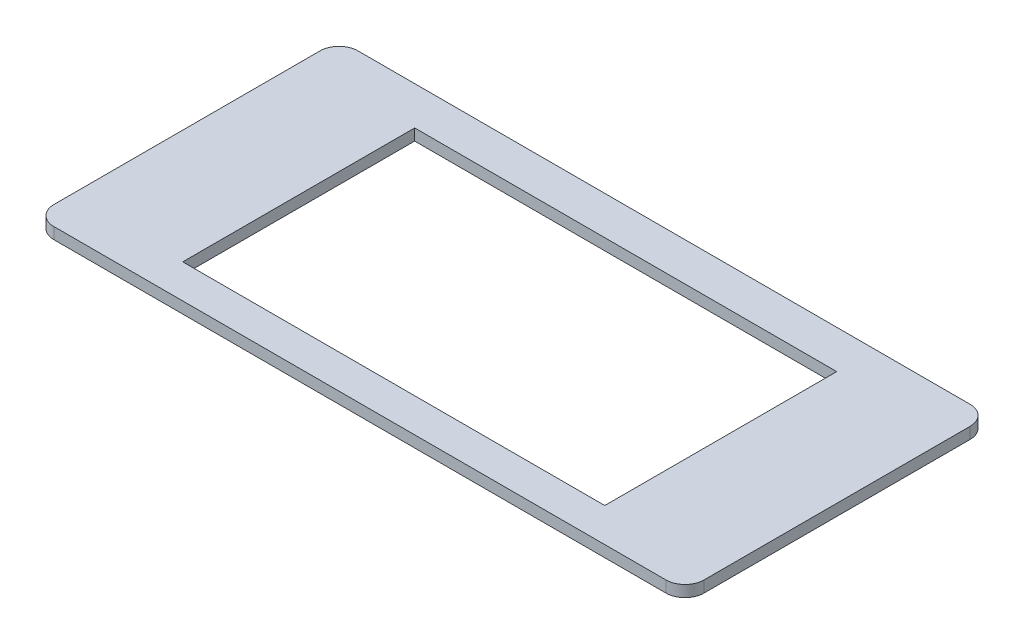
SolidWorks part; units mm, degrees
ref_plane "Front Plane" through (0, 0, 0) normal (0, 0, 1) x (1, 0, 0)
ref_plane "Top Plane" through (0, 0, 0) normal (0, 1, 0) x (1, 0, 0)
ref_plane "Right Plane" through (0, 0, 0) normal (1, 0, 0) x (0, 0, -1)
sketch "Sketch1" plane through (0, 0, 0) normal (0, 1, 0) x (1, 0, 0)
  line L1 (-75.3613, 38.6023) -> (85.6387, 38.6023)
  line L2 (-80.3613, 33.6023) -> (-80.3613, -36.3977)
  line L3 (-75.3613, -41.3977) -> (85.6387, -41.3977)
  line L4 (90.6387, 33.6023) -> (90.6387, -36.3977)
  arc A0 (-80.3613, 33.6023) -> (-75.3613, 38.6023) centre (-75.3613, 33.6023) cw
  arc A1 (-75.3613, -41.3977) -> (-80.3613, -36.3977) centre (-75.3613, -36.3977) cw
  arc A2 (85.6387, -41.3977) -> (90.6387, -36.3977) centre (85.6387, -36.3977) ccw
  arc A3 (85.6387, 38.6023) -> (90.6387, 33.6023) centre (85.6387, 33.6023) cw
  point P6 (-80.3613, 38.6023)
  point P11 (90.6387, -41.3977)
  point P14 (90.6387, 38.6023)
  dimension "D3" = 5
  dimension "D4" = 5
  dimension "D5" = 5
  dimension "D6" = 5
  dimension "D1" = 171
  dimension "D2" = 80
sketch "Sketch2" plane through (0, 0, 0) normal (0, 1, 0) x (1, 0, 0)
  line L1 (-50.3613, 28.5059) -> (60.6387, 28.5059)
  line L2 (-50.3613, 28.5059) -> (-50.3613, -32.4941)
  line L3 (-50.3613, -32.4941) -> (60.6387, -32.4941)
  line L4 (60.6387, 28.5059) -> (60.6387, -32.4941)
extrude "Boss-Extrude1" add sketch "Sketch1" along normal blind 3
extrude "Cut-Extrude1" cut sketch "Sketch2" against normal blind 3 and the other way blind 5
